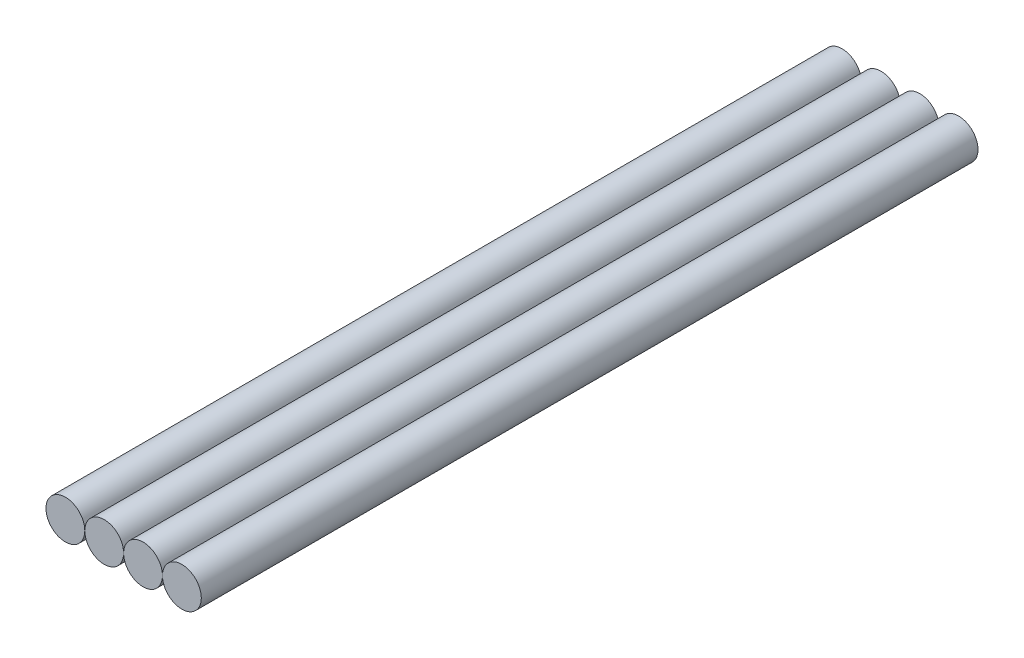
SolidWorks part; units mm, degrees
ref_plane "Plan de face" through (0, 0, 0) normal (0, 0, 1) x (1, 0, 0)
ref_plane "Plan de dessus" through (0, 0, 0) normal (0, 1, 0) x (1, 0, 0)
ref_plane "Plan de droite" through (0, 0, 0) normal (1, 0, 0) x (0, 0, -1)
sketch "Esquisse1" plane through (0, 0, 35) normal (0, 0, 1) x (1, 0, 0)
  line L0 (4.764, -8.6343) -> (4.764, -5.0293) construction
  line L1 (-10.2629, -8.6343) -> (19.7909, -8.6343) construction
  circle A0 centre (4.264, -7.6343) radius 0.5
  dimension "D1" = 1
  dimension "D2" = 0.5
  dimension "D3" = 1
extrude "Boss.-Extru.1" add sketch "Esquisse1" along normal mid plane 20
pattern_linear "Répétition linéaire1" count 3 spacing 1 along (1, 0, 0) count 2 spacing 1 along (-1, 0, 0) of "Boss.-Extru.1"
